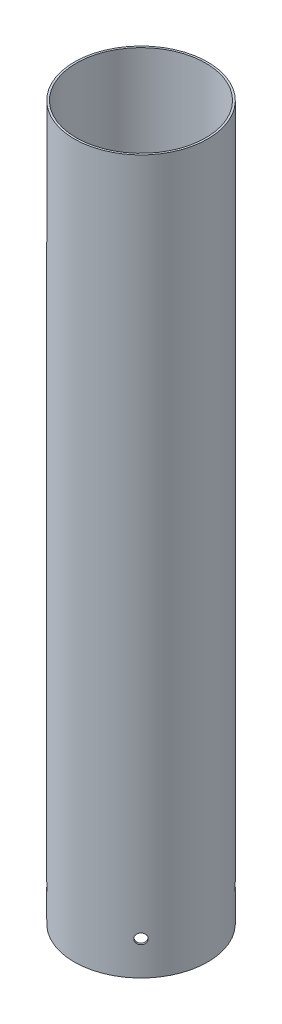
SolidWorks part; units mm, degrees
ref_plane "Front Plane" through (0, 0, 0) normal (0, 0, 1) x (1, 0, 0)
ref_plane "Top Plane" through (0, 0, 0) normal (0, 1, 0) x (1, 0, 0)
ref_plane "Right Plane" through (0, 0, 0) normal (1, 0, 0) x (0, 0, -1)
sketch "Sketch1" plane through (0, 0, 0) normal (0, 1, 0) x (1, 0, 0)
  circle A0 centre (0, 0) radius 38.15
  circle A1 centre (0, 0) radius 39.3
  dimension "D1" = 78.6
  dimension "D2" = 76.3
extrude "Boss-Extrude1" add sketch "Sketch1" along normal blind 420
ref_plane "Plane1" through (-27.7893, 0, 27.7893) normal (-0.7071, 0, 0.7071) x (0, -1, 0)
sketch "Sketch2" plane through (-27.7893, 0, 27.7893) normal (-0.7071, 0, 0.7071) x (0, -1, 0)
  line L0 (0, -39.3) -> (0, 39.3) construction
  circle A0 centre (-20, 0) radius 3
  dimension "D1" = 20
extrude "Cut-Extrude1" cut sketch "Sketch2" against normal up to next
pattern_circular "CirPattern1" count 4 over 360 about axis through (0, 420, 0) along (0, -1, 0) of "Cut-Extrude1"
